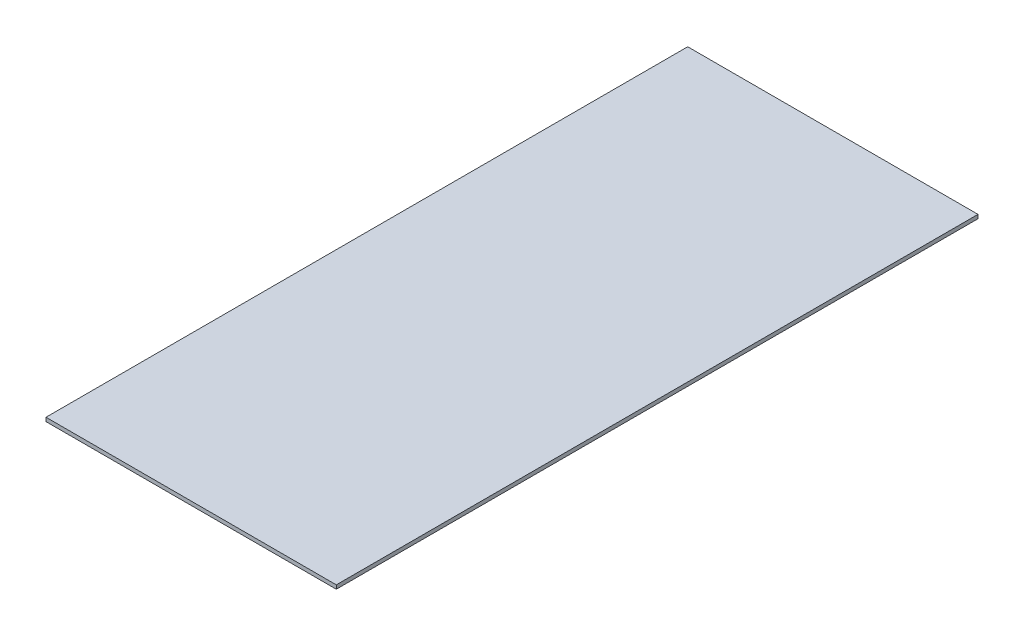
SolidWorks part; units mm, degrees
ref_plane "Front Plane" through (0, 0, 0) normal (0, 0, 1) x (1, 0, 0)
ref_plane "Top Plane" through (0, 0, 0) normal (0, 1, 0) x (1, 0, 0)
ref_plane "Right Plane" through (0, 0, 0) normal (1, 0, 0) x (0, 0, -1)
sketch "Sketch1" plane through (0, 0, 0) normal (0, 0, 1) x (1, 0, 0)
  line L1 (241.3, -3.175) -> (-241.3, -3.175)
  line L2 (241.3, -3.175) -> (241.3, 3.175)
  line L3 (241.3, 3.175) -> (-241.3, 3.175)
  line L4 (-241.3, -3.175) -> (-241.3, 3.175)
  line L5 (241.3, -3.175) -> (-241.3, 3.175) construction
  line L6 (241.3, 3.175) -> (-241.3, -3.175) construction
  point P0 (0, 0)
  dimension "D1" = 6.35
  dimension "D2" = 482.6
extrude "Boss-Extrude1" add sketch "Sketch1" along normal blind 1066.8
